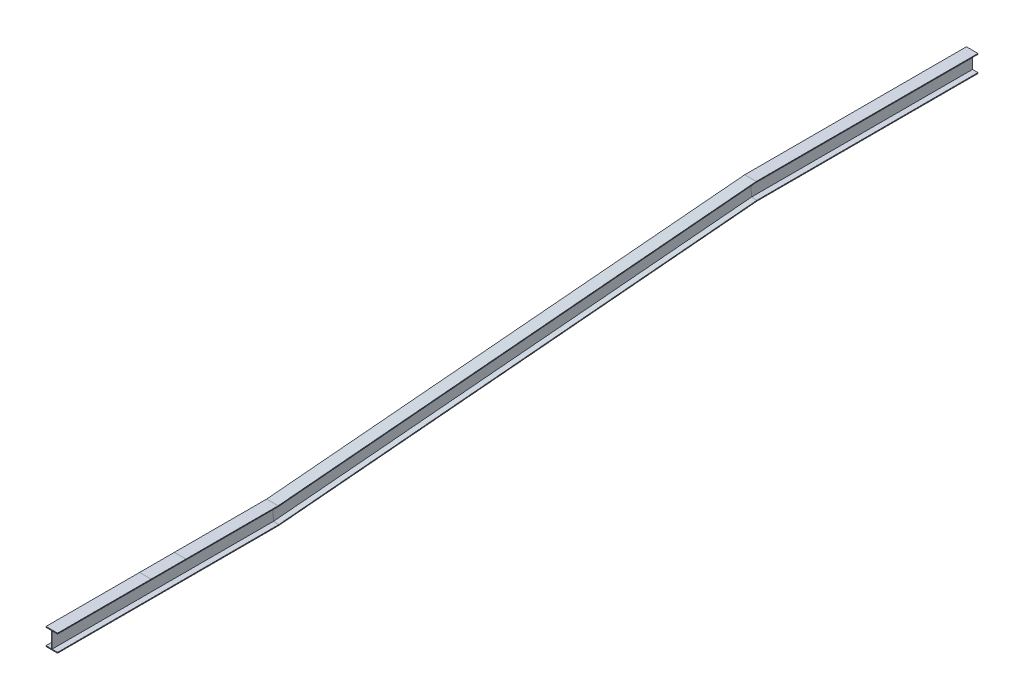
SolidWorks part; units mm, degrees
material "ASTM A992 Steel"
ref_plane "Front" through (0, 0, 0) normal (0, 0, 1) x (1, 0, 0)
ref_plane "Top" through (0, 0, 0) normal (0, 1, 0) x (1, 0, 0)
ref_plane "Right" through (0, 0, 0) normal (1, 0, 0) x (0, 0, -1)
sketch "Sketch1" plane through (0, 0, 0) normal (0, 0, 1) x (1, 0, 0)
  line L0 (0, -0.0002) -> (101.6, -0.0002)
  line L1 (101.6, -0.0002) -> (101.6, -7.1122)
  line L2 (101.6, -7.1122) -> (53.408, -7.1122)
  line L3 (53.408, -7.1122) -> (53.408, -146.0502)
  line L4 (53.408, -146.0502) -> (101.6, -146.0502)
  line L5 (101.6, -146.0502) -> (101.6, -153.1622)
  line L6 (101.6, -153.1622) -> (0, -153.1622)
  line L7 (0, -153.1622) -> (0, -146.0502)
  line L8 (0, -146.0502) -> (47.566, -146.0502)
  line L9 (47.566, -146.0502) -> (47.566, -7.1122)
  line L10 (47.566, -7.1122) -> (0, -7.1122)
  line L11 (0, -7.1122) -> (0, -0.0002)
  line L12 (50.8, -0.0002) -> (50.8, -153.1622) construction
  point P15 (50.8, -76.5812)
  dimension "D1" = 5.842
  dimension "D2" = 7.112
  dimension "D3" = 7.112
  dimension "D4" = 7.112
  dimension "D5" = 153.162
  dimension "D6" = 50.8
  dimension "D7" = 50.8
  dimension "D8" = 47.566
sketch "Sketch2" plane through (0, 0, 0) normal (1, 0, 0) x (0, 0, -1)
  line L0 (0, -76.5812) -> (1930, -76.5812)
  line L1 (1930, -76.5812) -> (6128.7777, 290.7642)
  line L2 (6128.7777, 290.7642) -> (8058.7777, 290.7642)
  line L3 (1930, -76.5812) -> (909.297, -76.5812) construction
  dimension "D1" = 5
  dimension "D2" = 1930
  dimension "D3" = 4214.8163
  dimension "D4" = 1930
sweep "Sweep1" add profiles "Sketch1" path "Sketch2"
sketch "Sketch3" plane through (0, -0.0002, 0) normal (0, 1, 0) x (1, 0, 0)
  line L0 (101.6, 0) -> (101.6, 1926.6564) construction
  line L1 (101.6, 963.3282) -> (101.6, 810.9282)
  line L2 (101.6, 810.9282) -> (0, 810.9282)
  line L3 (0, 0) -> (0, 1926.6564) construction
  line L4 (0, 810.9282) -> (0, 963.3282)
  line L5 (0, 963.3282) -> (0, 1115.7282)
  line L6 (0, 1115.7282) -> (101.6, 1115.7282)
  line L7 (101.6, 1115.7282) -> (101.6, 963.3282)
  point P0 (101.6, 963.3282)
  dimension "D1" = 152.4
  dimension "D2" = 152.4
split line "Split Line1"
sketch "Sketch4" plane through (0, 0, -8058.7777) normal (0, 0, -1) x (-1, 0, 0)
  line L12 (0, 360.2332) -> (0, 367.3452)
  line L13 (0, 367.3452) -> (-101.6, 367.3452)
  line L14 (-101.6, 367.3452) -> (-101.6, 360.2332)
  line L15 (-101.6, 360.2332) -> (-53.408, 360.2332)
  line L16 (-53.408, 360.2332) -> (-53.408, 221.2952)
  line L17 (-53.408, 221.2952) -> (-101.6, 221.2952)
  line L18 (-101.6, 221.2952) -> (-101.6, 214.1832)
  line L19 (-101.6, 214.1832) -> (0, 214.1832)
  line L20 (0, 214.1832) -> (0, 221.2952)
  line L21 (0, 221.2952) -> (-47.566, 221.2952)
  line L22 (-47.566, 221.2952) -> (-47.566, 360.2332)
  line L23 (-47.566, 360.2332) -> (0, 360.2332)
  line L24 (0, 360.2332) -> (0, 367.3452)
  line L25 (0, 367.3452) -> (-101.6, 367.3452)
  line L26 (-101.6, 367.3452) -> (-101.6, 360.2332)
  line L27 (-101.6, 360.2332) -> (-53.408, 360.2332)
  line L28 (-53.408, 360.2332) -> (-53.408, 221.2952)
  line L29 (-53.408, 221.2952) -> (-101.6, 221.2952)
  line L30 (-101.6, 221.2952) -> (-101.6, 214.1832)
  line L31 (-101.6, 214.1832) -> (0, 214.1832)
  line L32 (0, 214.1832) -> (0, 221.2952)
  line L33 (0, 221.2952) -> (-47.566, 221.2952)
  line L34 (-47.566, 221.2952) -> (-47.566, 360.2332)
  line L35 (-47.566, 360.2332) -> (0, 360.2332)
  dimension "D1" = 0
extrude "Boss-Extrude1" add sketch "Sketch4" along normal up to surface (14.5416 mm away)
sketch "Sketch5" plane through (0, 0, 0) normal (0, 0, 1) x (1, 0, 0)
  line L12 (0, -0.0002) -> (0, -7.1122)
  line L13 (0, -7.1122) -> (47.566, -7.1122)
  line L14 (47.566, -7.1122) -> (47.566, -146.0502)
  line L15 (47.566, -146.0502) -> (0, -146.0502)
  line L16 (0, -146.0502) -> (0, -153.1622)
  line L17 (0, -153.1622) -> (101.6, -153.1622)
  line L18 (101.6, -153.1622) -> (101.6, -146.0502)
  line L19 (101.6, -146.0502) -> (53.408, -146.0502)
  line L20 (53.408, -146.0502) -> (53.408, -7.1122)
  line L21 (53.408, -7.1122) -> (101.6, -7.1122)
  line L22 (101.6, -7.1122) -> (101.6, -0.0002)
  line L23 (101.6, -0.0002) -> (0, -0.0002)
  line L24 (0, -0.0002) -> (0, -7.1122)
  line L25 (0, -7.1122) -> (47.566, -7.1122)
  line L26 (47.566, -7.1122) -> (47.566, -146.0502)
  line L27 (47.566, -146.0502) -> (0, -146.0502)
  line L28 (0, -146.0502) -> (0, -153.1622)
  line L29 (0, -153.1622) -> (101.6, -153.1622)
  line L30 (101.6, -153.1622) -> (101.6, -146.0502)
  line L31 (101.6, -146.0502) -> (53.408, -146.0502)
  line L32 (53.408, -146.0502) -> (53.408, -7.1122)
  line L33 (53.408, -7.1122) -> (101.6, -7.1122)
  line L34 (101.6, -7.1122) -> (101.6, -0.0002)
  line L35 (101.6, -0.0002) -> (0, -0.0002)
  dimension "D1" = 0
extrude "Boss-Extrude2" add sketch "Sketch5" along normal up to surface (11.1092 mm away)
sketch "Sketch6" plane through (0, 0, -8073.3193) normal (0, 0, -1) x (-1, 0, 0)
  line L12 (-47.566, 221.2952) -> (-47.566, 360.2332)
  line L13 (-47.566, 360.2332) -> (0, 360.2332)
  line L14 (0, 360.2332) -> (0, 367.3452)
  line L15 (0, 367.3452) -> (-101.6, 367.3452)
  line L16 (-101.6, 367.3452) -> (-101.6, 360.2332)
  line L17 (-101.6, 360.2332) -> (-53.408, 360.2332)
  line L18 (-53.408, 360.2332) -> (-53.408, 221.2952)
  line L19 (-53.408, 221.2952) -> (-101.6, 221.2952)
  line L20 (-101.6, 221.2952) -> (-101.6, 214.1832)
  line L21 (-101.6, 214.1832) -> (0, 214.1832)
  line L22 (0, 214.1832) -> (0, 221.2952)
  line L23 (0, 221.2952) -> (-47.566, 221.2952)
  line L24 (-47.566, 221.2952) -> (-47.566, 360.2332)
  line L25 (-47.566, 360.2332) -> (0, 360.2332)
  line L26 (0, 360.2332) -> (0, 367.3452)
  line L27 (0, 367.3452) -> (-101.6, 367.3452)
  line L28 (-101.6, 367.3452) -> (-101.6, 360.2332)
  line L29 (-101.6, 360.2332) -> (-53.408, 360.2332)
  line L30 (-53.408, 360.2332) -> (-53.408, 221.2952)
  line L31 (-53.408, 221.2952) -> (-101.6, 221.2952)
  line L32 (-101.6, 221.2952) -> (-101.6, 214.1832)
  line L33 (-101.6, 214.1832) -> (0, 214.1832)
  line L34 (0, 214.1832) -> (0, 221.2952)
  line L35 (0, 221.2952) -> (-47.566, 221.2952)
  dimension "D1" = 0
extrude "Boss-Extrude4" [suppressed] add sketch "Sketch6" along normal up to surface (73.152 mm away)
